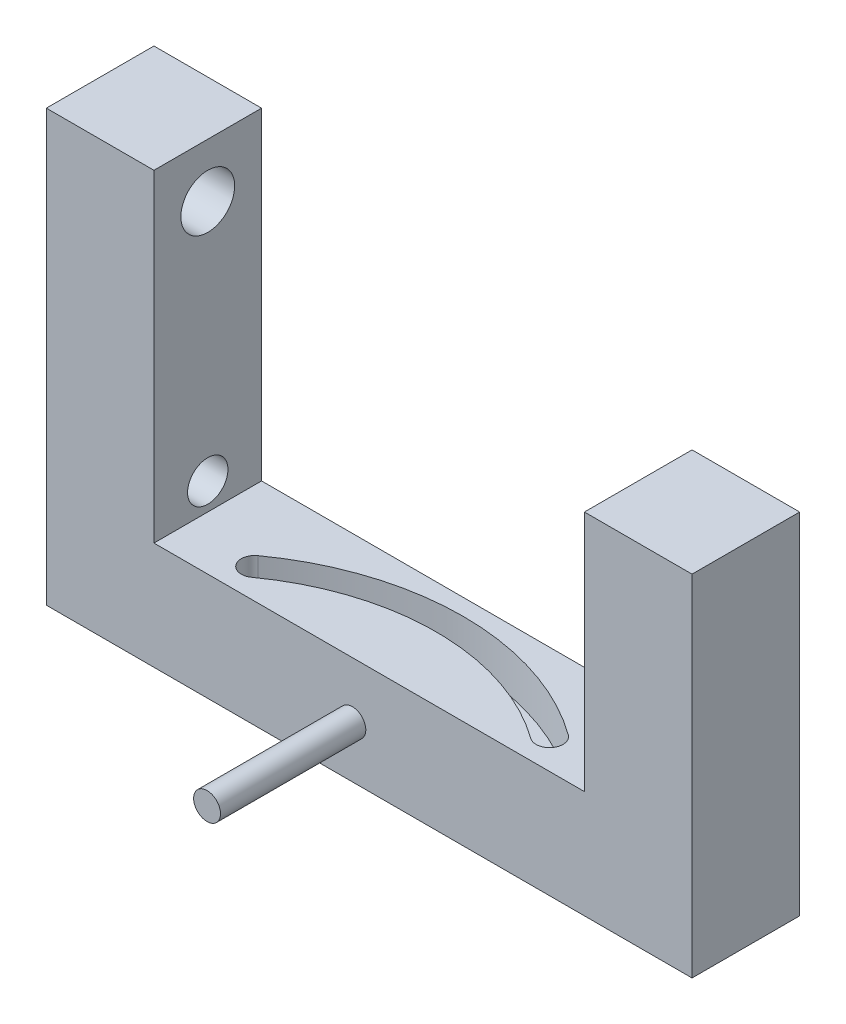
SolidWorks part; units mm, degrees
ref_plane "Front Plane" through (0, 0, 0) normal (0, 0, 1) x (1, 0, 0)
ref_plane "Top Plane" through (0, 0, 0) normal (0, 1, 0) x (1, 0, 0)
ref_plane "Right Plane" through (0, 0, 0) normal (1, 0, 0) x (0, 0, -1)
sketch "Sketch1" plane through (0, 0, 0) normal (0, 0, 1) x (1, 0, 0)
  line L0 (0, 0) -> (0, 203.2)
  line L1 (0, 203.2) -> (50.8, 203.2)
  line L2 (50.8, 203.2) -> (50.8, 50.8)
  line L3 (50.8, 50.8) -> (254, 50.8)
  line L4 (254, 50.8) -> (254, 165.1)
  line L5 (254, 165.1) -> (304.8, 165.1)
  line L6 (304.8, 165.1) -> (304.8, 0)
  line L7 (304.8, 0) -> (0, 0)
  dimension "D1" = 203.2
  dimension "D2" = 50.8
  dimension "D3" = 50.8
  dimension "D4" = 203.2
  dimension "D5" = 38.1
extrude "Boss-Extrude1" add sketch "Sketch1" along normal mid plane 50.8
sketch "Sketch2" plane through (0, 0, 0) normal (-1, 0, 0) x (0, 0, 1)
  line L0 (0, 177.8) -> (0, 203.2) construction
  line L1 (25.4, 203.2) -> (-25.4, 203.2) construction
  circle A0 centre (0, 177.8) radius 12.7
  dimension "D2" = 25.4
  dimension "D1" = 25.4
extrude "Cut-Extrude1" cut sketch "Sketch2" against normal up to next
sketch "Sketch3" plane through (0, 0, 0) normal (-1, 0, 0) x (0, 0, 1)
  line L0 (0, 63.5) -> (0, 0) construction
  circle A0 centre (0, 63.5) radius 9.525
  dimension "D1" = 19.05
  dimension "D2" = 63.5
extrude "Cut-Extrude2" cut sketch "Sketch3" against normal blind 50.8
sketch "Sketch4" plane through (0, 0, 25.4) normal (0, 0, 1) x (1, 0, 0)
  circle A0 centre (144.45, 24.4041) radius 6.35
  dimension "D1" = 12.7
extrude "Boss-Extrude2" add sketch "Sketch4" along normal blind 68.58
sketch "Sketch5" plane through (0, 50.8, 0) normal (0, 1, 0) x (1, 0, 0)
  arc A0 (84.1464, -11.1769) -> (223.3072, -11.1769) centre (153.7268, -107.6968) cw construction
  arc A1 (227.0206, -6.0258) -> (80.433, -6.0258) centre (153.7268, -107.6968) ccw
  arc A2 (219.5938, -16.328) -> (87.8598, -16.328) centre (153.7268, -107.6968) ccw
  arc A3 (219.5938, -16.328) -> (227.0206, -6.0258) centre (223.3072, -11.1769) ccw
  arc A4 (80.433, -6.0258) -> (87.8598, -16.328) centre (84.1464, -11.1769) ccw
  point P3 (153.7268, 11.2886)
  dimension "D1" = 6.35
extrude "Cut-Extrude3" cut sketch "Sketch5" against normal blind 19.05
